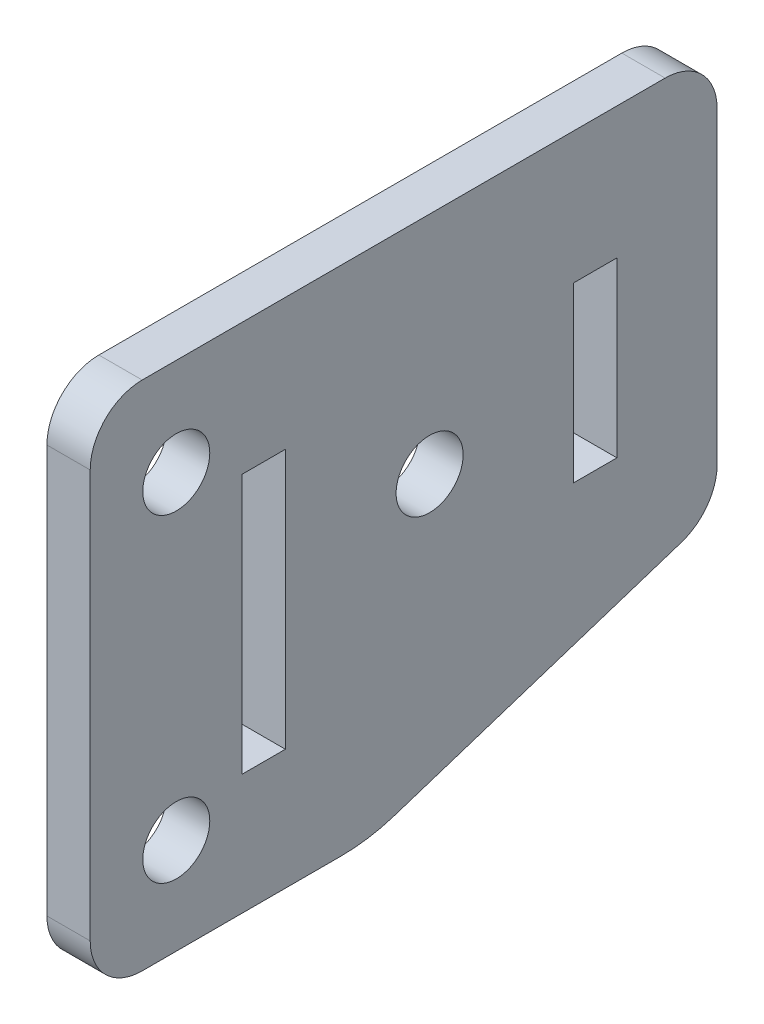
SolidWorks part; units mm, degrees
material "AISI 4340 Steel, annealed"
ref_plane "X-Y Datum" through (0, 0, 0) normal (0, 0, 1) x (1, 0, 0)
ref_plane "X-Z Datum" through (0, 0, 0) normal (0, 1, 0) x (1, 0, 0)
ref_plane "Y-Z Datum" through (0, 0, 0) normal (1, 0, 0) x (0, 0, -1)
sketch "Sketch1" plane through (0, 0, 0) normal (1, 0, 0) x (0, 0, -1)
  line L2 (-11.43, 25.4) -> (-57.404, 25.4)
  line L3 (-57.404, 25.4) -> (-57.404, -12.131)
  line L4 (0, 0) -> (-50000, 0) construction
  line L5 (0, 0) -> (0, 50000) construction
  line L6 (-38.9981, -12.131) -> (-39.2035, -12.131) construction
  line L7 (-35.0766, -11.5105) -> (-1.9116, -0.7438) construction
  line L8 (-38.9981, -12.131) -> (-39.2035, -12.131)
  line L9 (-35.0766, -11.5105) -> (-11.43, -3.8338)
  line L10 (-39.2035, -12.131) -> (-63.5, -12.131) construction
  line L11 (-39.2035, -12.131) -> (-57.404, -12.131)
  line L13 (-11.43, -3.8338) -> (-11.43, 25.4)
  line L14 (0, -0.2833) -> (0, 25.4) construction
  line L15 (0, 25.4) -> (-118.0696, 25.4) construction
  arc A0 (-38.9981, -12.131) -> (-35.0766, -11.5105) centre (-38.9981, 0.569) ccw construction
  arc A1 (-38.9981, -12.131) -> (-35.0766, -11.5105) centre (-38.9981, 0.569) ccw
  dimension "D2" = 57.404
  dimension "D3" = 11.43
extrude "Boss-Extrude1" add sketch "Sketch1" against normal blind 3.175
hole_wizard "#10 (0.1935) Diameter Hole1" positions "Sketch2" profile "Sketch3" hole size "#10" standard "ANSI Inch"
sketch "Sketch2" plane through (0, 0, 0) normal (1, 0, 0) x (0, 0, -1)
  line L2 (-11.43, 25.4) -> (-57.404, 25.4) construction
  line L4 (-46.2661, 25.4) -> (-46.2661, 15.748) construction
  line L5 (-46.2661, -3.302) -> (-46.2661, -12.1412) construction
  line L7 (-57.404, 25.4) -> (-57.404, -12.131) construction
  point P0 (-51.0921, -5.08)
  point P2 (-51.0921, 18.288)
  point P4 (-32.512, 8.89)
  dimension "D1" = 4.826
  dimension "D2" = 30.48
  dimension "D3" = 4.826
  dimension "D4" = 7.112
  dimension "D6" = 16.51
sketch "Sketch3" plane through (0, -5.08, 51.0921) normal (0, 1, 0) x (0, 0, -1)
  line L0 (0, 0) -> (0, 12.6526)
  line L1 (0, 12.6526) -> (2.4574, 11.176)
  line L2 (2.4574, 11.176) -> (2.4574, 0)
  line L5 (2.4574, 0) -> (0, 0)
  line L10 (0, 12.6526) -> (-2.4575, 11.176) construction
  line L11 (0, -6.35) -> (0, 107.95) construction
  dimension "Hole Dia." = 4.9149
  dimension "Hole Depth" = 11.176
  dimension "Drill Angle" = 118
sketch "Sketch6" plane through (-3.175, 0, 0) normal (-1, 0, 0) x (0, 0, 1)
  line L0 (46.2661, 15.748) -> (46.2661, -3.302)
  line L1 (46.2661, -3.302) -> (43.0911, -3.302)
  line L2 (43.0911, -3.302) -> (43.0911, 15.748)
  line L3 (43.0911, 15.748) -> (46.2661, 15.748)
  line L4 (21.9521, 15.748) -> (18.7771, 15.748)
  line L5 (18.7771, 15.748) -> (18.7771, 3.048)
  line L6 (18.7771, 3.048) -> (21.9521, 3.048)
  line L7 (21.9521, 3.048) -> (21.9521, 15.748)
extrude "Cut-Extrude1" cut sketch "Sketch6" against normal through all
fillet "Fillet1" radius 3.81 4 edges at (-1.5875, 25.4, 57.404) (-1.5875, -12.131, 57.404) (-1.5875, 25.4, 11.43) (-1.5875, -3.8338, 11.43)
